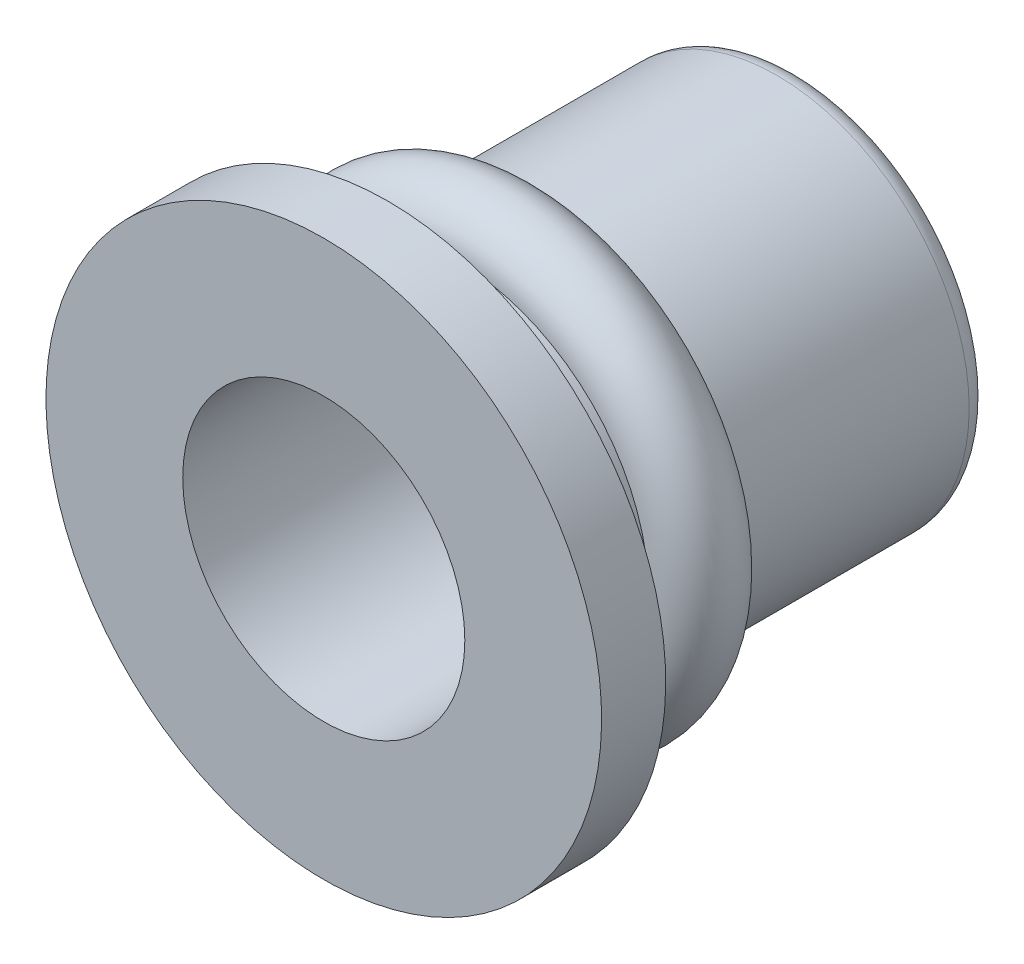
SolidWorks part; units mm, degrees
material "Cobre"
ref_plane "Plano frontal" through (0, 0, 0) normal (0, 0, 1) x (1, 0, 0)
ref_plane "Plano superior" through (0, 0, 0) normal (0, 1, 0) x (1, 0, 0)
ref_plane "Plano direito" through (0, 0, 0) normal (1, 0, 0) x (0, 0, -1)
sketch "Esboço1" plane through (0, 0, 0) normal (1, 0, 0) x (0, 0, -1)
  line L0 (0, 0) -> (0, 6.5)
  line L1 (0, 6.5) -> (1.5, 6.5)
  line L2 (1.5, 6.5) -> (1.5, 4.5)
  line L3 (1.5, 4.5) -> (3.1, 4.5)
  line L4 (5.1, 4.5) -> (10.6, 4.5)
  line L5 (11.1, 4) -> (11.1, 0)
  line L6 (11.1, 0) -> (0, 0)
  arc A0 (3.1, 4.5) -> (5.1, 4.5) centre (4.1, 4.5) cw
  arc A1 (11.1, 4) -> (10.6, 4.5) centre (10.6, 4) ccw
  point P12 (11.1, 4.5)
  dimension "D3" = 1
  dimension "D8" = 0.5
  dimension "D1" = 1.5
  dimension "D2" = 1.6
  dimension "D4" = 6
  dimension "D5" = 6.5
  dimension "D6" = 4.5
  dimension "D7" = 4.5
revolve "Revolução1" add sketch "Esboço1" angle 360 about L6
hole_wizard "Furo com folga de M61" positions "Esboço3" profile "Esboço2" hole size "M6" standard "ISO" end condition through all
sketch "Esboço3" plane through (0, 0, 0) normal (0, 0, 1) x (1, 0, 0)
  point P0 (0, 0)
sketch "Esboço2" plane through (0, 0, 0) normal (1, 0, 0) x (0, -1, 0)
  line L0 (0, 0) -> (0, 11.1)
  line L1 (0, 11.1) -> (3.3, 11.1)
  line L2 (3.3, 11.1) -> (3.3, 0)
  line L5 (3.3, 0) -> (0, 0)
  line L11 (0, -6.35) -> (0, 107.95) construction
  dimension "Thru Hole Dia." = 6.6
  dimension "Thru Hole Depth" = 11.1
